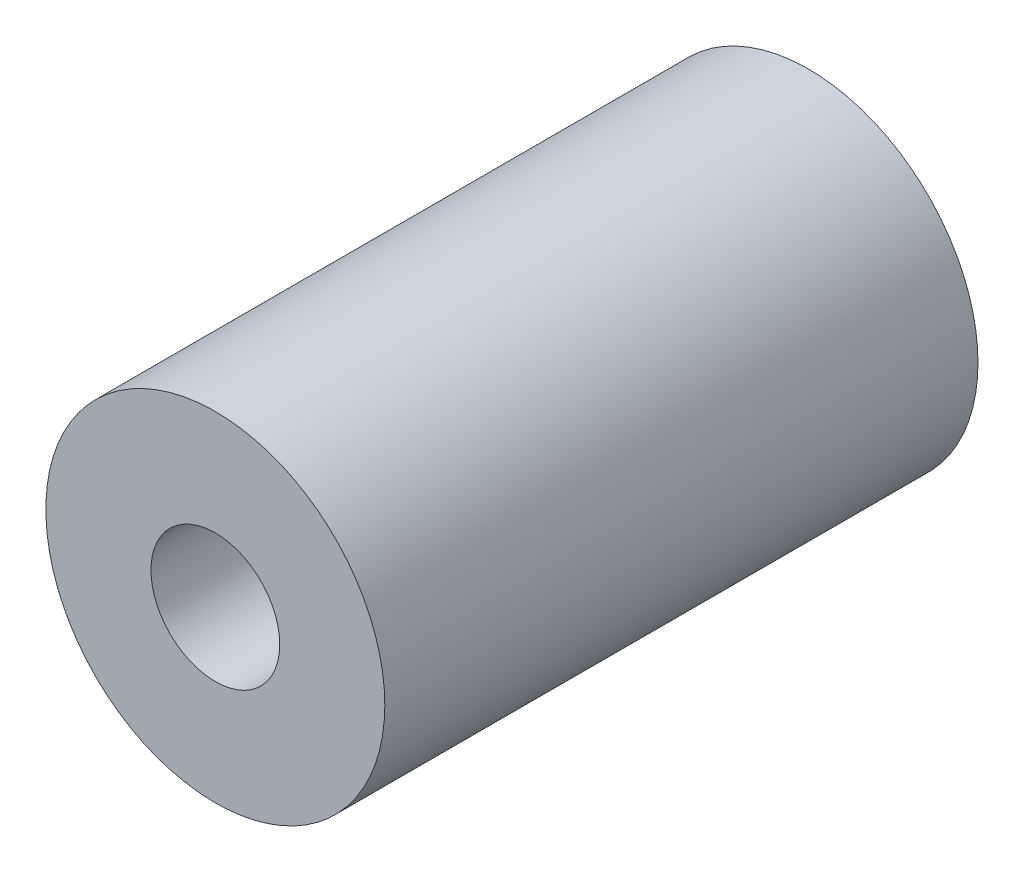
SolidWorks part; units mm, degrees
ref_plane "Front Plane" through (0, 0, 0) normal (0, 0, 1) x (1, 0, 0)
ref_plane "Top Plane" through (0, 0, 0) normal (0, 1, 0) x (1, 0, 0)
ref_plane "Right Plane" through (0, 0, 0) normal (1, 0, 0) x (0, 0, -1)
sketch "Sketch1" plane through (0, 0, 0) normal (0, 0, 1) x (1, 0, 0)
  circle A0 centre (0, 0) radius 6.35
  circle A1 centre (0, 0) radius 2.413
  dimension "D1" = 12.7
  dimension "D2" = 4.826
extrude "Boss-Extrude1" add sketch "Sketch1" along normal mid plane 22.225
